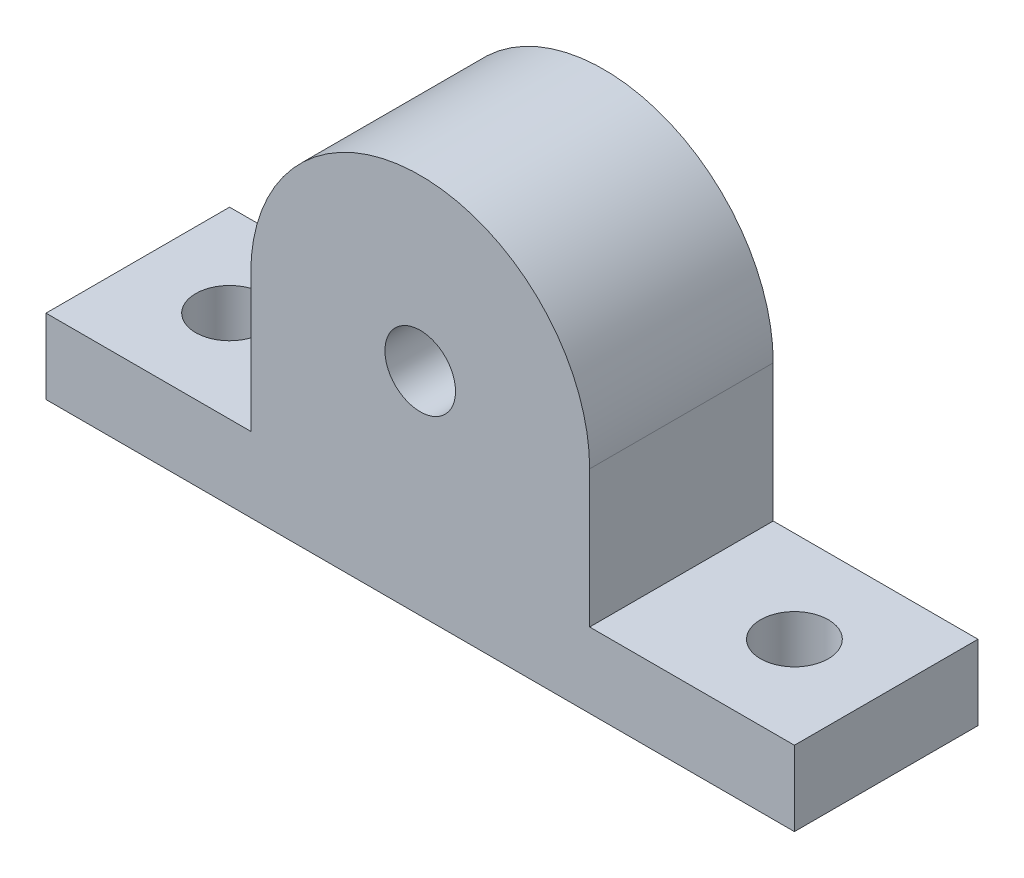
SolidWorks part; units mm, degrees
ref_plane "前视基准面" through (0, 0, 0) normal (0, 0, 1) x (1, 0, 0)
ref_plane "上视基准面" through (0, 0, 0) normal (0, 1, 0) x (1, 0, 0)
ref_plane "右视基准面" through (0, 0, 0) normal (1, 0, 0) x (0, 0, -1)
sketch "草图1" plane through (0, 0, 0) normal (0, 0, 1) x (1, 0, 0)
  line L0 (-12, -9.7) -> (-26.5, -9.7)
  line L2 (12, 0) -> (12, -9.7)
  line L4 (-12, 0) -> (-12, -9.7)
  line L5 (26.5, -9.7) -> (12, -9.7)
  line L6 (26.5, -9.7) -> (26.5, -15)
  line L7 (26.5, -15) -> (-26.5, -15)
  line L8 (-26.5, -9.7) -> (-26.5, -15)
  arc A1 (12, 0) -> (-12, 0) centre (0, 0) ccw
  point P11 (-12, -17.9547)
  dimension "D2" = 15
  dimension "D1" = 12
  dimension "D3" = 53
  dimension "D4" = 5.3
  dimension "D5" = 26.5
  dimension "D6" = 9.7
extrude "凸台-拉伸1" add sketch "草图1" along normal blind 13
sketch "草图2" plane through (0, 0, 13) normal (0, 0, 1) x (1, 0, 0)
  circle A0 centre (0, 0) radius 2.5
  dimension "D1" = 5
extrude "切除-拉伸1" cut sketch "草图2" against normal blind 13
sketch "草图3" plane through (0, -9.7, 0) normal (0, 1, 0) x (1, 0, 0)
  line L0 (26.5, -13) -> (26.5, 0) construction
  line L1 (26.5, 0) -> (12, 0) construction
  line L2 (-12, 0) -> (-26.5, 0) construction
  circle A0 centre (20, -6.5) radius 2.4
  circle A1 centre (-20, -6.5) radius 2.4
  dimension "D1" = 4.8
  dimension "D2" = 4.8
  dimension "D3" = 40
  dimension "D4" = 6.5
  dimension "D5" = 6.5
  dimension "D6" = 6.5
extrude "切除-拉伸2" cut sketch "草图3" against normal blind 13
